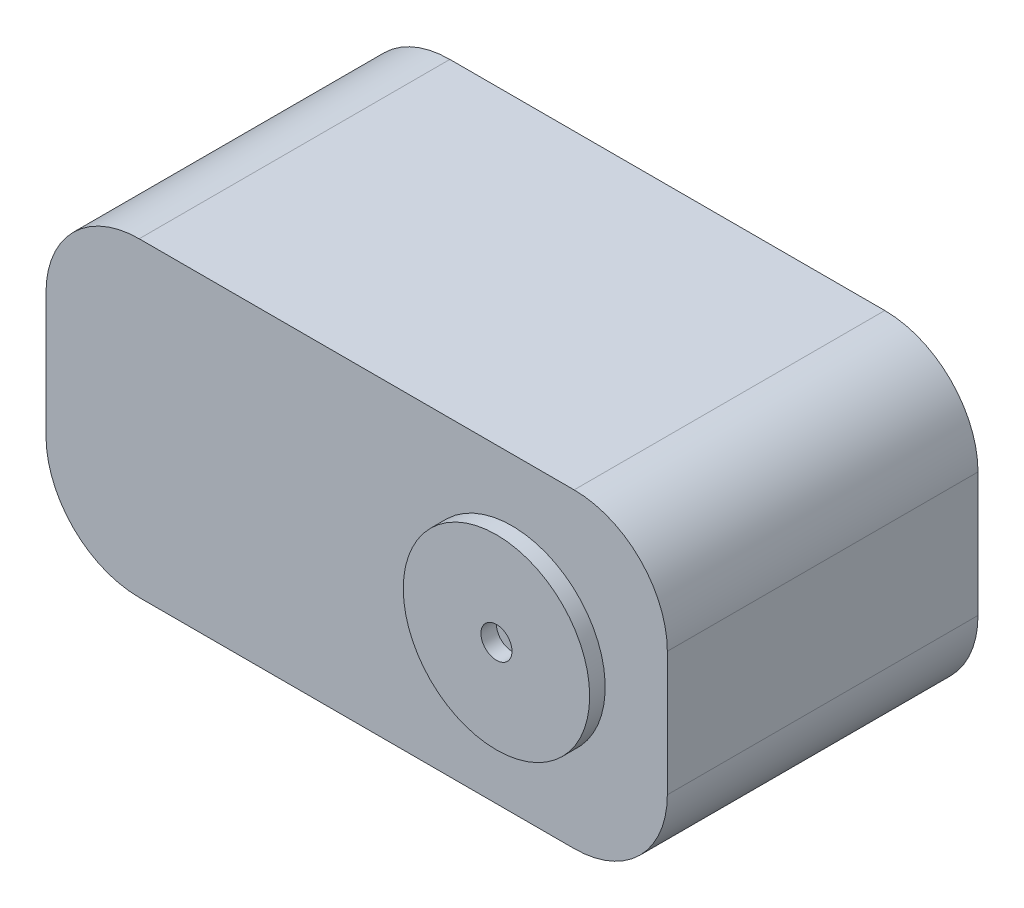
SolidWorks part; units mm, degrees
ref_plane "Front Plane" through (0, 0, 0) normal (0, 0, 1) x (1, 0, 0)
ref_plane "Top Plane" through (0, 0, 0) normal (0, 1, 0) x (1, 0, 0)
ref_plane "Right Plane" through (0, 0, 0) normal (1, 0, 0) x (0, 0, -1)
sketch "Sketch1" plane through (0, 0, 0) normal (0, 0, 1) x (1, 0, 0)
  line L1 (-17.78, 12.7) -> (17.78, 12.7)
  line L2 (-25.4, 5.08) -> (-25.4, -5.08)
  line L3 (-17.78, -12.7) -> (17.78, -12.7)
  line L4 (25.4, 5.08) -> (25.4, -5.08)
  arc A0 (-25.4, -5.08) -> (-17.78, -12.7) centre (-17.78, -5.08) ccw
  arc A1 (-17.78, 12.7) -> (-25.4, 5.08) centre (-17.78, 5.08) ccw
  arc A2 (17.78, -12.7) -> (25.4, -5.08) centre (17.78, -5.08) ccw
  arc A3 (17.78, 12.7) -> (25.4, 5.08) centre (17.78, 5.08) cw
  point P4 (26.1081, -10.2391)
  point P5 (0, 12.7)
  point P7 (25.4, 0)
  point P12 (-25.4, 12.7)
  point P15 (25.4, -12.7)
  point P18 (25.4, 12.7)
  dimension "D3" = 7.62
  dimension "D1" = 50.8
  dimension "D2" = 25.4
extrude "Boss-Extrude1" add sketch "Sketch1" along normal blind 25.4 contours A1 L2 A0 L3 A2 L4 A3 L1
sketch "Sketch2" plane through (0, 0, 25.4) normal (0, 0, 1) x (1, 0, 0)
  line L0 (25.4, 5.08) -> (25.4, -5.08) construction
  circle A0 centre (12.7, 0) radius 7.62
  point P2 (11.9703, 0)
  point P5 (12.7, 0)
  point P6 (25.4, 0)
  dimension "D1" = 15.24
  dimension "D2" = 12.7
extrude "Boss-Extrude2" add sketch "Sketch2" along normal blind 1.27
sketch "Sketch3" plane through (0, 0, 26.67) normal (0, 0, 1) x (1, 0, 0)
  circle A0 centre (12.7, 0) radius 1.27
  point P2 (12.5116, 0)
  point P3 (6.6532, 0)
  dimension "D1" = 2.54
extrude "Cut-Extrude1" cut sketch "Sketch3" against normal blind 1.27
